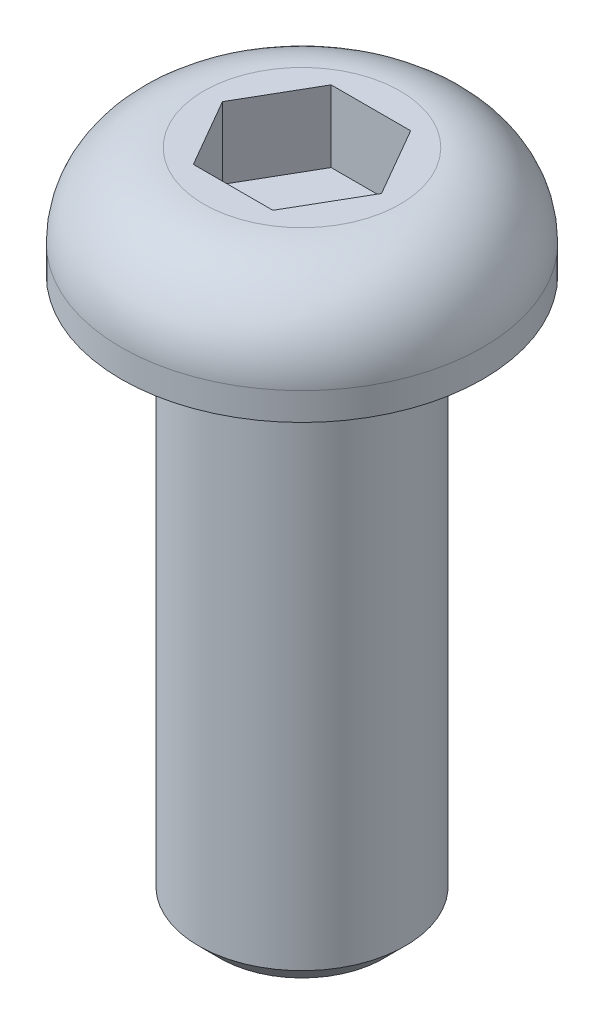
SolidWorks part; units mm, degrees
material "Plain Carbon Steel"
ref_plane "Front Plane" through (0, 0, 0) normal (0, 0, 1) x (1, 0, 0)
ref_plane "Top Plane" through (0, 0, 0) normal (0, 1, 0) x (1, 0, 0)
ref_plane "Right Plane" through (0, 0, 0) normal (1, 0, 0) x (0, 0, -1)
sketch "Sketch1" plane through (0, 0, 0) normal (0, 0, 1) x (1, 0, 0)
  line L0 (0, 0) -> (2.85, 0)
  line L1 (5.25, -2.4) -> (5.25, -3.2)
  line L2 (5.25, -3.2) -> (3, -3.2)
  line L3 (3, -3.2) -> (3, -19.2)
  line L4 (3, -19.2) -> (0, -19.2)
  line L5 (0, -19.2) -> (0, 0)
  line L6 (0, 5) -> (0, -24.2) construction
  arc A0 (2.85, 0) -> (5.25, -2.4) centre (2.85, -2.4) cw
  dimension "D1" = 5
  dimension "D2" = 5
  dimension "D3" = 6
  dimension "D4" = 10.5
  dimension "D5" = 3.2
  dimension "D6" = 0.8
  dimension "L" = 16
revolve "Revolve1" add sketch "Sketch1" angle 360 about L6
sketch "Sketch2" plane through (0, 0, 0) normal (0, 1, 0) x (1, 0, 0)
  line L1 (2.3094, 0) -> (1.1547, 2)
  line L2 (1.1547, 2) -> (-1.1547, 2)
  line L3 (-1.1547, 2) -> (-2.3094, 0)
  line L4 (-2.3094, 0) -> (-1.1547, -2)
  line L5 (-1.1547, -2) -> (1.1547, -2)
  line L6 (1.1547, -2) -> (2.3094, 0)
  circle A0 centre (0, 0) radius 2 construction
  dimension "D1" = 4
extrude "Cut-Extrude1" cut sketch "Sketch2" against normal blind 2.08
fillet "Fillet1" radius 0.25 1 edges at (-3, -3.2, 0)
chamfer "Chamfer1" distance 0.625 angle 45 1 edges at (-3, -19.2, 0)
cosmetic thread "Cosmetic Thread1" parameters "B"=5, "D2"=4.891
